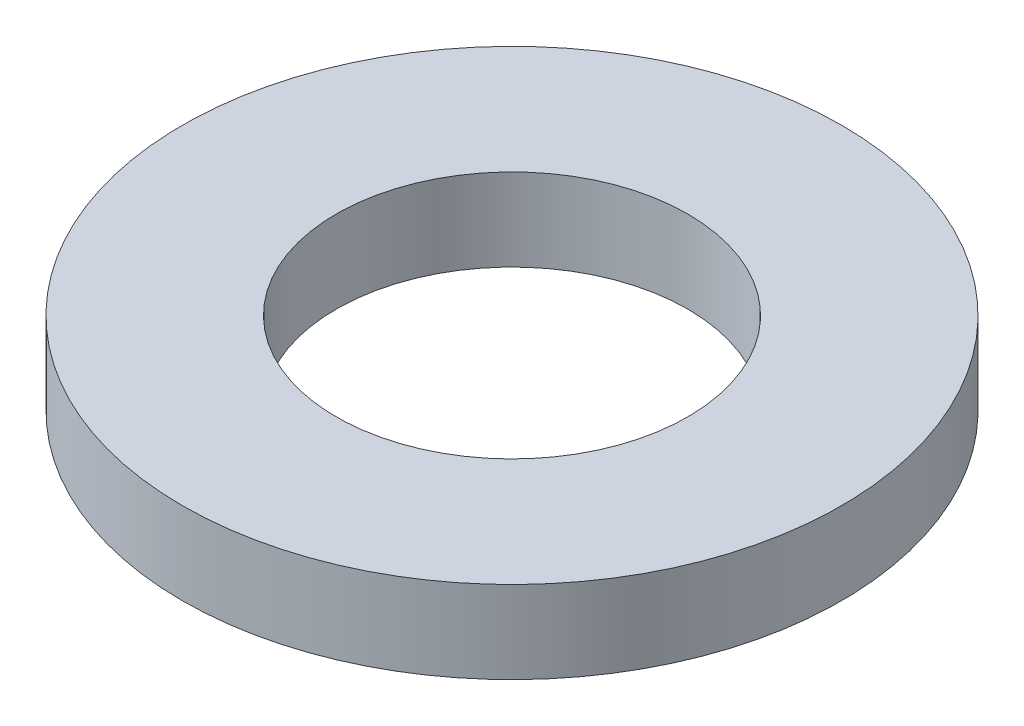
SolidWorks part; units mm, degrees
material "Cast Stainless Steel"
ref_plane "Front Plane" through (0, 0, 0) normal (0, 0, 1) x (1, 0, 0)
ref_plane "Top Plane" through (0, 0, 0) normal (0, 1, 0) x (1, 0, 0)
ref_plane "Right Plane" through (0, 0, 0) normal (1, 0, 0) x (0, 0, -1)
sketch "Sketch1" plane through (0, 0, 0) normal (0, 1, 0) x (1, 0, 0)
  circle A0 centre (0, 0) radius 6
  circle A1 centre (0, 0) radius 3.2
  dimension "D1" = 12
  dimension "D2" = 6.4
extrude "Boss-Extrude1" add sketch "Sketch1" along normal blind 1.5
move or copy body "Body-Move/Copy1" bodies to move or copy 101
